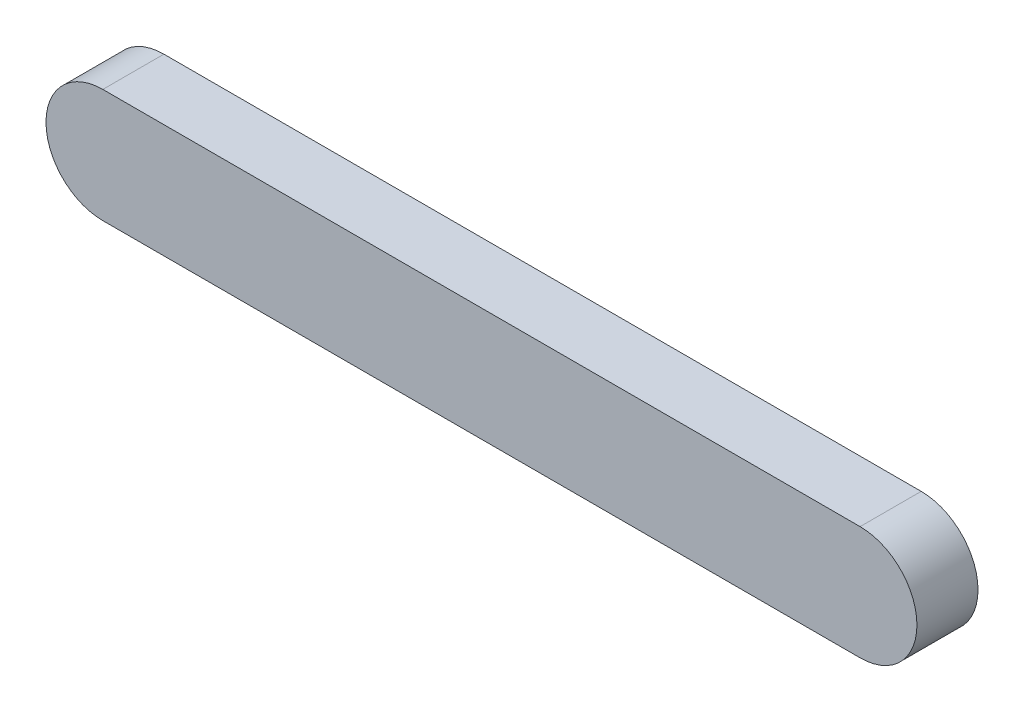
SolidWorks part; units mm, degrees
ref_plane "Front Plane" through (0, 0, 0) normal (0, 0, 1) x (1, 0, 0)
ref_plane "Top Plane" through (0, 0, 0) normal (0, 1, 0) x (1, 0, 0)
ref_plane "Right Plane" through (0, 0, 0) normal (1, 0, 0) x (0, 0, -1)
sketch "Sketch1" plane through (0, 0, 0) normal (0, 0, 1) x (1, 0, 0)
  line L0 (69.4661, 0) -> (-54.5339, 0) construction
  line L1 (69.4661, -9.3054) -> (-54.5339, -9.3054)
  line L2 (69.4661, 9.3054) -> (-54.5339, 9.3054)
  arc A0 (69.4661, -9.3054) -> (69.4661, 9.3054) centre (69.4661, 0) ccw
  arc A1 (-54.5339, 9.3054) -> (-54.5339, -9.3054) centre (-54.5339, 0) ccw
  point P3 (7.4661, 0)
  dimension "D2" = 9.3054
  dimension "D1" = 124
extrude "Boss-Extrude1" add sketch "Sketch1" along normal blind 10
